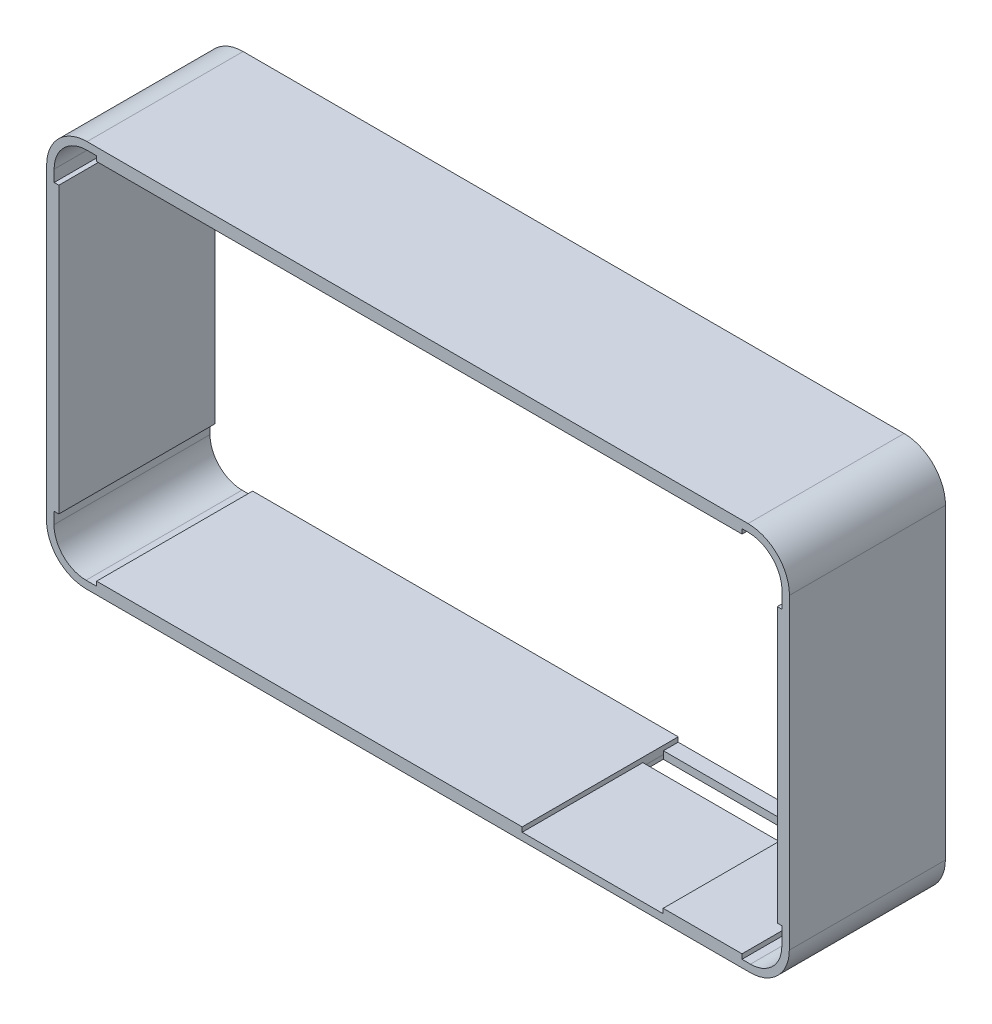
SolidWorks part; units mm, degrees
ref_plane "前视基准面" through (0, 0, 0) normal (0, 0, 1) x (1, 0, 0)
ref_plane "上视基准面" through (0, 0, 0) normal (0, 1, 0) x (1, 0, 0)
ref_plane "右视基准面" through (0, 0, 0) normal (1, 0, 0) x (0, 0, -1)
other "Configuration Table"
sketch "草图1" plane through (0, 0, 0) normal (0, 0, 1) x (1, 0, 0)
  line L0 (2.8555, -1.3873) -> (5.8004, -1.3887) construction
  line L1 (-1.3859, 5.784) -> (-1.3873, 2.8595) construction
  line L2 (-1.3859, 5.784) -> (-1.3731, 32.9796) construction
  line L3 (-1.3718, 35.8005) -> (-1.3731, 32.9796) construction
  line L4 (5.7751, 40.121) -> (2.9541, 40.1224) construction
  line L5 (5.7751, 40.121) -> (70.9893, 40.0903) construction
  line L6 (73.6932, 40.089) -> (70.9893, 40.0903) construction
  line L7 (78.1252, 32.9586) -> (78.1265, 35.6516) construction
  line L8 (78.1252, 32.9586) -> (78.1124, 5.7404) construction
  line L9 (78.111, 2.7586) -> (78.1124, 5.7404) construction
  line L10 (70.9853, -1.4194) -> (73.9277, -1.4208) construction
  line L11 (70.9853, -1.4194) -> (5.8004, -1.3887) construction
  line L12 (2.8555, -1.3873) -> (5.8004, -1.3887)
  line L13 (-1.3859, 5.784) -> (-1.3873, 2.8595)
  line L14 (-1.3859, 5.784) -> (-1.3731, 32.9796)
  line L15 (-1.3718, 35.8005) -> (-1.3731, 32.9796)
  line L16 (5.7751, 40.121) -> (2.9541, 40.1224)
  line L17 (5.7751, 40.121) -> (70.9893, 40.0903)
  line L18 (73.6932, 40.089) -> (70.9893, 40.0903)
  line L19 (78.1252, 32.9586) -> (78.1265, 35.6516)
  line L20 (78.1252, 32.9586) -> (78.1124, 5.7404)
  line L21 (78.111, 2.7586) -> (78.1124, 5.7404)
  line L22 (70.9853, -1.4194) -> (73.9277, -1.4208)
  line L23 (70.9853, -1.4194) -> (5.8004, -1.3887)
  line L25 (70.9887, 38.7903) -> (70.9893, 40.0903) construction
  line L26 (70.9889, 39.2903) -> (5.7747, 39.321)
  line L27 (5.7751, 40.121) -> (5.7744, 38.821) construction
  line L28 (5.7747, 39.321) -> (2.9455, 39.321)
  line L29 (-0.5718, 35.8054) -> (-0.5873, 2.8435)
  line L30 (2.8402, -0.5873) -> (73.9507, -0.6208)
  line L31 (77.3109, 2.7363) -> (77.3265, 35.6689)
  line L32 (73.6896, 39.289) -> (70.9889, 39.2903)
  arc A0 (-1.3873, 2.8595) -> (2.8555, -1.3873) centre (2.8575, 2.8575) ccw construction
  arc A1 (2.9541, 40.1224) -> (-1.3718, 35.8005) centre (2.9521, 35.7985) ccw construction
  arc A2 (78.1265, 35.6516) -> (73.6932, 40.089) centre (73.6911, 35.6537) ccw construction
  arc A3 (73.9277, -1.4208) -> (78.111, 2.7586) centre (73.9296, 2.7605) ccw construction
  arc A4 (-1.3873, 2.8595) -> (2.8555, -1.3873) centre (2.8575, 2.8575) ccw
  arc A5 (2.9541, 40.1224) -> (-1.3718, 35.8005) centre (2.9521, 35.7985) ccw
  arc A6 (78.1265, 35.6516) -> (73.6932, 40.089) centre (73.6911, 35.6537) ccw
  arc A7 (73.9277, -1.4208) -> (78.111, 2.7586) centre (73.9296, 2.7605) ccw
  arc A8 (2.9455, 39.321) -> (-0.5718, 35.8054) centre (2.9455, 35.8038) ccw
  arc A9 (-0.5873, 2.8435) -> (2.8402, -0.5873) centre (2.8418, 2.8419) ccw
  arc A10 (73.9507, -0.6208) -> (77.3109, 2.7363) centre (73.9523, 2.7379) ccw
  arc A11 (77.3265, 35.6689) -> (73.6896, 39.289) centre (73.708, 35.6706) ccw
  dimension "D1" = 0.8
  dimension "D2" = 0.8
  dimension "D3" = 0.8
  dimension "D4" = 0.8
extrude "凸台-拉伸1" add sketch "草图1" along normal blind 16.7
sketch "草图3" plane through (-0.0003, -0.5859, 0) normal (0.0005, 1, 0) x (1, -0.0005, 0)
  line L1 (64.6138, -3.7899) -> (49.514, -3.7899)
  line L2 (64.6138, -3.7899) -> (64.6138, -1.5862)
  line L3 (64.6138, -1.5862) -> (49.514, -1.5862)
  line L4 (49.514, -3.7899) -> (49.514, -1.5862)
extrude "切除-拉伸1" cut sketch "草图3" against normal blind 5
sketch "草图4" plane through (0, 0, 0) normal (0, 0, 1) x (1, 0, 0)
  line L0 (2.8402, -0.5873) -> (73.9507, -0.6208) construction
  line L5 (77.3109, 2.7363) -> (77.3265, 35.6689) construction
  line L6 (77.3119, 4.7594) -> (76.9246, 4.7594)
  line L7 (77.3119, 4.7594) -> (77.3119, 7.7594)
  line L8 (77.3119, 7.7594) -> (76.9246, 7.7594)
  line L9 (76.9246, 4.7594) -> (76.9246, 7.7594)
  line L10 (-0.5718, 35.8054) -> (-0.5873, 2.8435) construction
  line L11 (28.7669, -0.5995) -> (31.7669, -0.5995)
  line L12 (28.7669, -0.5995) -> (28.7669, -0.2164)
  line L13 (28.7669, -0.2164) -> (31.7669, -0.2164)
  line L14 (31.7669, -0.5995) -> (31.7669, -0.2164)
  line L19 (-0.5853, 7.1876) -> (-0.1853, 7.1876)
  line L20 (-0.5853, 7.1876) -> (-0.5853, 4.1876)
  line L21 (-0.5853, 4.1876) -> (-0.1853, 4.1876)
  line L22 (-0.1853, 7.1876) -> (-0.1853, 4.1876)
  line L23 (73.6896, 39.289) -> (5.7747, 39.321) construction
  line L24 (-0.5741, 30.999) -> (-0.1853, 30.999)
  line L25 (-0.5741, 30.999) -> (-0.5741, 33.999)
  line L26 (-0.5741, 33.999) -> (-0.1853, 33.999)
  line L27 (-0.1853, 30.999) -> (-0.1853, 33.999)
  line L28 (23.3728, 39.3127) -> (26.3728, 39.3127)
  line L29 (23.3728, 39.3127) -> (23.3728, 38.9127)
  line L30 (23.3728, 38.9127) -> (26.3728, 38.9127)
  line L31 (26.3728, 39.3127) -> (26.3728, 38.9127)
  line L33 (47.6153, 39.3013) -> (50.6153, 39.3013)
  line L34 (47.6153, 39.3013) -> (47.6153, 38.9127)
  line L35 (47.6153, 38.9127) -> (50.6153, 38.9127)
  line L36 (50.6153, 39.3013) -> (50.6153, 38.9127)
  line L37 (77.3246, 31.813) -> (76.9246, 31.813)
  line L38 (77.3246, 31.813) -> (77.3246, 28.813)
  line L39 (77.3246, 28.813) -> (76.9246, 28.813)
  line L40 (76.9246, 31.813) -> (76.9246, 28.813)
  line L42 (49.5135, -1.1839) -> (49.5135, 1.731) construction
  line L43 (49.5134, -1.4093) -> (49.5138, -0.6093) construction
  line L44 (64.6135, -0.6164) -> (67.9895, -0.6164)
  line L45 (64.6135, -0.6164) -> (64.6135, -0.2164)
  line L46 (64.6135, -0.2164) -> (67.9895, -0.2164)
  line L47 (67.9895, -0.6164) -> (67.9895, -0.2164)
  line L48 (49.5138, -0.6093) -> (46.7914, -0.6093)
  line L49 (49.5138, -0.6093) -> (49.5138, -0.2164)
  line L50 (49.5138, -0.2164) -> (46.7914, -0.2164)
  line L51 (46.7914, -0.6093) -> (46.7914, -0.2164)
  line L52 (3.9417, -0.5878) -> (7.1686, -0.5878)
  line L53 (3.9417, -0.5878) -> (3.9417, -0.2164)
  line L54 (3.9417, -0.2164) -> (7.1686, -0.2164)
  line L55 (7.1686, -0.5878) -> (7.1686, -0.2164)
  dimension "D1" = 3
  dimension "D2" = 0.4
  dimension "D3" = 0.4
  dimension "D4" = 0.4
  dimension "D5" = 0.4
extrude "凸台-拉伸2" add sketch "草图4" along normal blind 16.7
sketch "草图5" plane through (0, 0, 0) normal (0, 0, -1) x (-1, 0, 0)
  line L9 (-2.8402, -0.5873) -> (-46.7914, -0.608) construction
  line L14 (-77.3109, 2.7363) -> (-77.3232, 28.813) construction
  line L19 (-77.6225, 33.9631) -> (-76.8257, 33.9631)
  line L20 (-73.6896, 39.289) -> (-50.6153, 39.2999) construction
  line L21 (-77.6225, 33.9631) -> (-77.6225, 4.6247)
  line L23 (-862.1323, 38.9175) -> (-862.1323, 38.4175)
  line L26 (-77.6225, 4.6247) -> (-76.8118, 4.6247)
  line L31 (-76.8257, 33.9631) -> (-76.8118, 4.6247)
  line L32 (0.5741, 30.999) -> (0.5873, 2.8435) construction
  line L37 (-73.0503, -0.9611) -> (-64.6135, -0.9611)
  line L38 (-23.3728, 39.3127) -> (-5.7747, 39.321) construction
  line L39 (-73.0503, 39.811) -> (-3.9736, 39.811)
  line L40 (-73.0503, 39.811) -> (-73.0503, 38.7893)
  line L41 (-73.0503, 38.7893) -> (-3.9736, 38.8219)
  line L42 (-3.9736, 39.811) -> (-3.9736, 38.8219)
  line L43 (-73.0503, -0.9611) -> (-73.0503, -0.1093)
  line L44 (-49.5224, -0.9611) -> (-3.9732, -0.9611)
  line L45 (-49.5224, -0.9611) -> (-49.5224, -0.1093)
  line L46 (-49.5224, -0.1093) -> (-3.9732, -0.0878)
  line L47 (-3.9732, -0.9611) -> (-3.9732, -0.0878)
  line L48 (-73.0503, -0.1093) -> (-64.6135, -0.1093)
  line L49 (-64.6135, -0.9611) -> (-64.6135, -0.1093)
  line L50 (1.2516, 34.5662) -> (0.0724, 34.5662)
  line L51 (1.2516, 34.5662) -> (1.2516, 4.0929)
  line L52 (1.2516, 4.0929) -> (0.0867, 4.0929)
  line L53 (0.0724, 34.5662) -> (0.0867, 4.0929)
  dimension "D1" = 0.5
  dimension "D2" = 0.5
  dimension "D3" = 0.5
  dimension "D4" = 0.5
sketch "草图6" plane through (0, 0, 16.7) normal (0, 0, 1) x (1, 0, 0)
  line L1 (76.8257, 33.9631) -> (77.6225, 33.9631)
  line L2 (76.8257, 33.9631) -> (76.8257, 4.6247)
  line L3 (76.8257, 4.6247) -> (77.6225, 4.6247)
  line L4 (77.6225, 33.9631) -> (77.6225, 4.6247)
  line L5 (64.6135, -0.1093) -> (73.0503, -0.1093)
  line L6 (64.6135, -0.1093) -> (64.6135, -0.9611)
  line L7 (64.6135, -0.9611) -> (73.0503, -0.9611)
  line L8 (73.0503, -0.1093) -> (73.0503, -0.9611)
  line L9 (49.5224, -0.1093) -> (3.9732, -0.1093)
  line L10 (49.5224, -0.1093) -> (49.5224, -0.9611)
  line L11 (49.5224, -0.9611) -> (3.9732, -0.9611)
  line L12 (3.9732, -0.1093) -> (3.9732, -0.9611)
  line L13 (-0.0724, 34.5662) -> (-1.2516, 34.5662)
  line L14 (-0.0724, 34.5662) -> (-0.0724, 4.0929)
  line L15 (-0.0724, 4.0929) -> (-1.2516, 4.0929)
  line L16 (-1.2516, 34.5662) -> (-1.2516, 4.0929)
  line L17 (3.9736, 39.811) -> (73.0503, 39.811)
  line L18 (3.9736, 39.811) -> (3.9736, 38.7893)
  line L19 (3.9736, 38.7893) -> (73.0503, 38.7893)
  line L20 (73.0503, 39.811) -> (73.0503, 38.7893)
extrude "凸台-拉伸3" add sketch "草图6" against normal up to surface (16.7 mm away)
